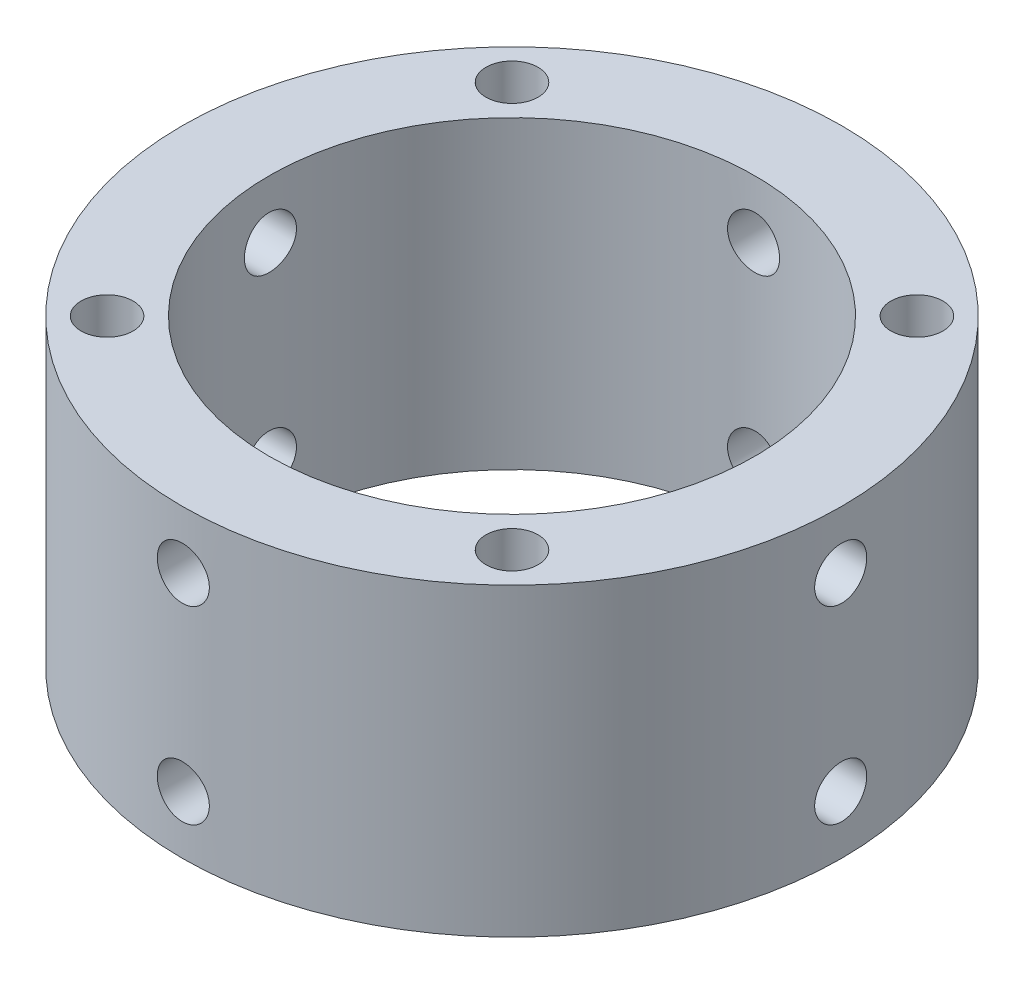
SolidWorks part; units mm, degrees
ref_plane "Front Plane" through (0, 0, 0) normal (0, 0, 1) x (1, 0, 0)
ref_plane "Top Plane" through (0, 0, 0) normal (0, 1, 0) x (1, 0, 0)
ref_plane "Right Plane" through (0, 0, 0) normal (1, 0, 0) x (0, 0, -1)
sketch "Sketch1" plane through (0, 0, 0) normal (0, 1, 0) x (1, 0, 0)
  circle A0 centre (0, 0) radius 28.5
  circle A1 centre (0, 0) radius 21
  dimension "D1" = 57
  dimension "D2" = 42
extrude "Boss-Extrude1" add sketch "Sketch1" along normal mid plane 26.35
sketch "Sketch2" plane through (0, 0, 0) normal (0, 0, 1) x (1, 0, 0)
  line L0 (-28.5, 0) -> (28.5, 0) construction
  line L1 (-28.5, 13.175) -> (-28.5, -13.175) construction
  line L2 (28.5, -13.175) -> (28.5, 13.175) construction
  circle A0 centre (0, 8.175) radius 2.25
  circle A1 centre (0, -8.175) radius 2.25
  dimension "D1" = 4.5
  dimension "D2" = 16.35
extrude "Cut-Extrude1" cut sketch "Sketch2" against normal through all
pattern_circular "CirPattern1" count 4 every 90 about axis through (0, 13.175, 0) along (0, -1, 0) of "Cut-Extrude1"
sketch "Sketch3" plane through (0, 13.175, 0) normal (0, 1, 0) x (1, 0, 0)
  line L0 (0, 0) -> (20.1525, 20.1525) construction
  line L1 (0, 0) -> (28.5, 0) construction
  line L2 (14.8492, 14.8492) -> (20.1525, 20.1525) construction
  circle A0 centre (0, 0) radius 28.5 construction
  circle A1 centre (0, 0) radius 21 construction
  circle A2 centre (17.5009, 17.5009) radius 2.25
  circle A3 centre (17.5009, -17.5009) radius 2.25
  circle A4 centre (-17.5009, -17.5009) radius 2.25
  circle A5 centre (-17.5009, 17.5009) radius 2.25
  point P5 (14.8492, 14.8492)
  point P7 (20.1525, 20.1525)
  point P10 (17.5009, 17.5009)
  point P12 (17.5009, 17.5009)
  point P15 (-15.8348, 14.344)
  point P16 (0, 0)
  point P17 (0, 0)
  point P24 (0, 0)
  dimension "D3" = 4.5
  dimension "D1" = 45
  dimension "D2" = 7.5
  dimension "D4" = 4
extrude "Cut-Extrude2" cut sketch "Sketch3" against normal through all
